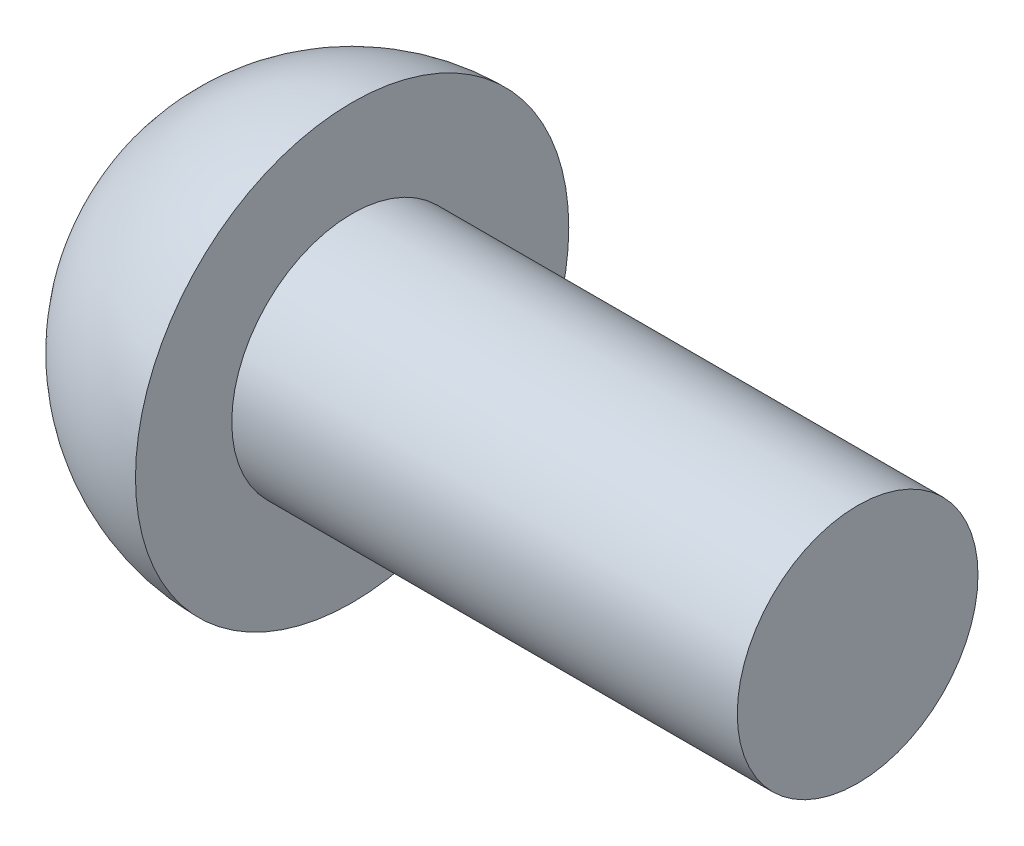
SolidWorks part; units mm, degrees
material "Oak"
ref_plane "Front" through (0, 0, 0) normal (0, 0, 1) x (1, 0, 0)
ref_plane "Top" through (0, 0, 0) normal (0, 1, 0) x (1, 0, 0)
ref_plane "Right" through (0, 0, 0) normal (1, 0, 0) x (0, 0, -1)
sketch "Sketch1" plane through (0, 0, 0) normal (0, 0, 1) x (1, 0, 0)
  line L0 (0, 0) -> (0, 5)
  line L1 (0, 5) -> (-21, 5)
  line L2 (-21, 5) -> (-21, 9)
  line L3 (-30, 0) -> (0, 0) construction
  line L4 (0, 0) -> (-30, 0)
  arc A0 (-21, 9) -> (-30, 0) centre (-21, 0) ccw
  dimension "D1" = 9
  dimension "D2" = 21
  dimension "D3" = 10
revolve "Revolve1" add sketch "Sketch1" angle 360 about L3
